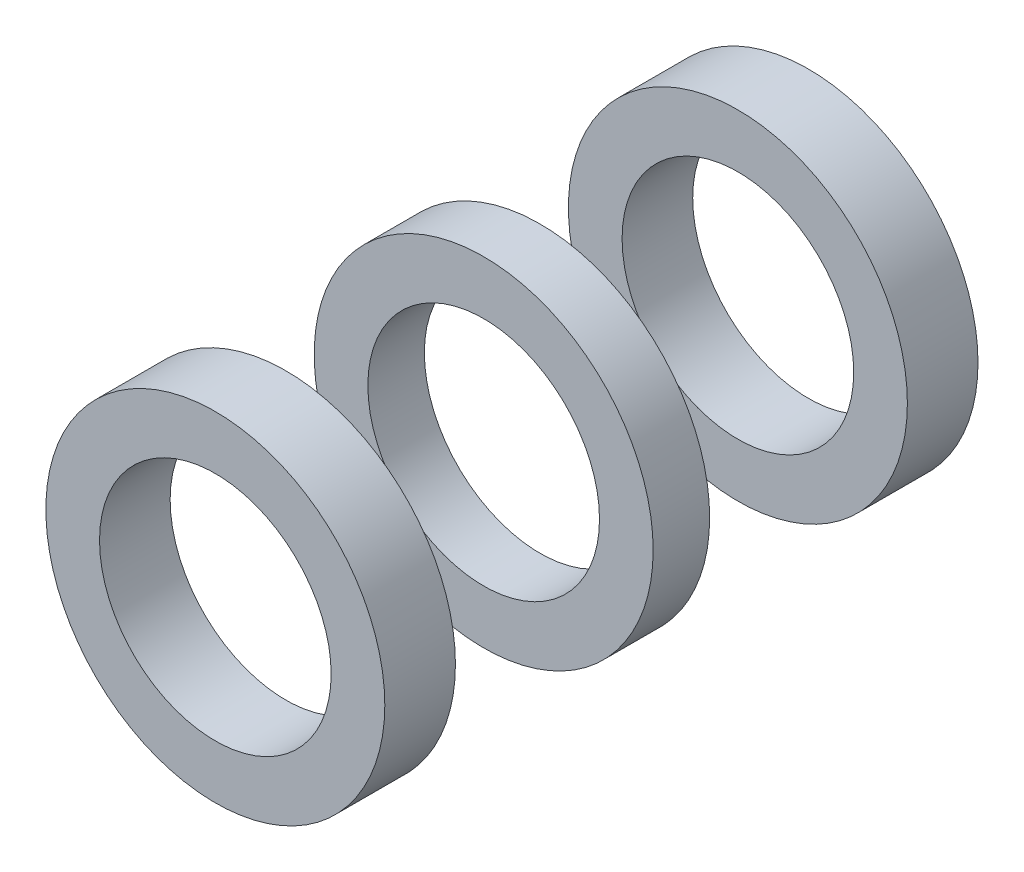
SolidWorks part; units mm, degrees
ref_plane "Спереди" through (0, 0, 0) normal (0, 0, 1) x (1, 0, 0)
ref_plane "Сверху" through (0, 0, 0) normal (0, 1, 0) x (1, 0, 0)
ref_plane "Справа" through (0, 0, 0) normal (1, 0, 0) x (0, 0, -1)
sketch "Эскиз1" plane through (0, 0, 0) normal (0, 0, 1) x (1, 0, 0)
  circle A0 centre (0, 0) radius 6
  circle A1 centre (0, 0) radius 4.1
extrude "Rear" add sketch "Эскиз1" along normal blind 2.5 from offset 34.5 separate body
sketch "Эскиз2" plane through (0, 0, 0) normal (0, 0, 1) x (1, 0, 0)
  circle A0 centre (0, 0) radius 6
  circle A1 centre (0, 0) radius 4.1
extrude "Middle" add sketch "Эскиз2" along normal blind 2 from offset 44 separate body
sketch "Эскиз3" plane through (0, 0, 0) normal (0, 0, 1) x (1, 0, 0)
  circle A0 centre (0, 0) radius 6
  circle A1 centre (0, 0) radius 4.1
extrude "Front" add sketch "Эскиз3" along normal blind 2.5 from offset 53 separate body
